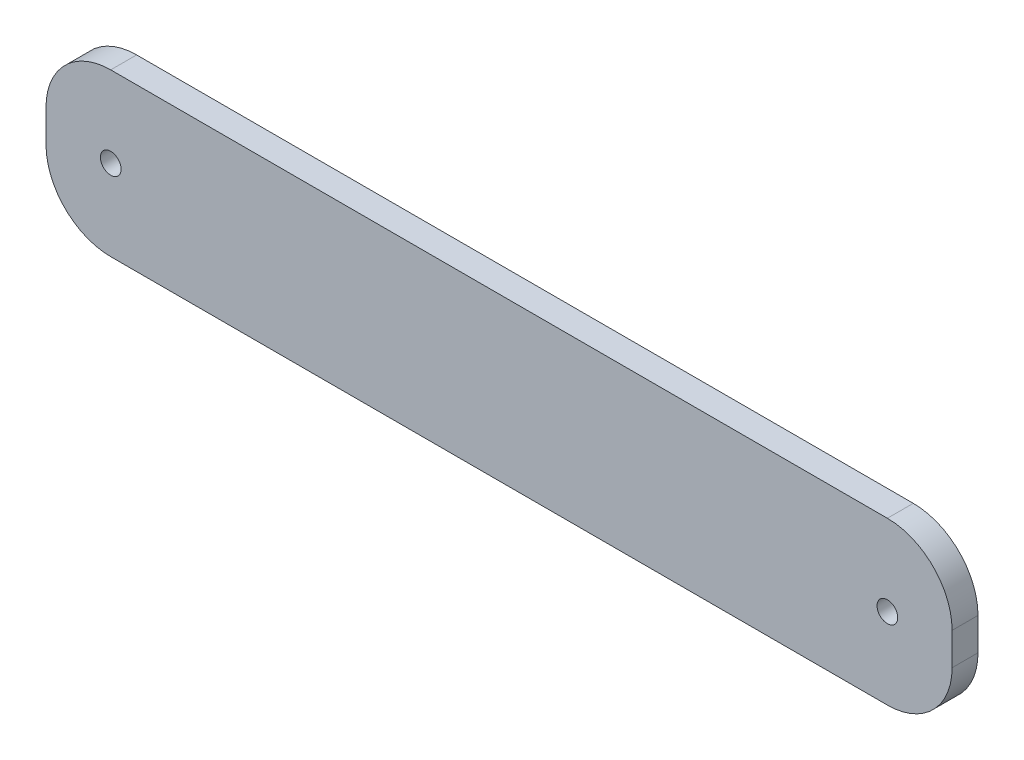
SolidWorks part; units mm, degrees
ref_plane "前视基准面" through (0, 0, 0) normal (0, 0, 1) x (1, 0, 0)
ref_plane "上视基准面" through (0, 0, 0) normal (0, 1, 0) x (1, 0, 0)
ref_plane "右视基准面" through (0, 0, 0) normal (1, 0, 0) x (0, 0, -1)
sketch "草图1" plane through (0, 0, 0) normal (0, 0, 1) x (1, 0, 0)
  line L0 (-70, 0) -> (70, 0) construction
  line L1 (-70, -12.5) -> (70, -12.5)
  line L2 (-70, -12.5) -> (-70, 12.5)
  line L3 (-70, 12.5) -> (70, 12.5)
  line L4 (70, -12.5) -> (70, 12.5)
  line L5 (-70, -12.5) -> (70, 12.5) construction
  line L6 (-70, 12.5) -> (70, -12.5) construction
  circle A0 centre (-60, 0) radius 1.6
  circle A1 centre (60, 0) radius 1.6
  point P0 (0, 0)
  dimension "D3" = 3.2
  dimension "D4" = 10
  dimension "D5" = 3.2
  dimension "D6" = 10
  dimension "D1" = 140
  dimension "D2" = 25
extrude "凸台-拉伸1" add sketch "草图1" along normal blind 4
fillet "圆角1" radius 10 4 edges at (-70, 12.5, 2) (-70, -12.5, 2) (70, -12.5, 2) (70, 12.5, 2)
